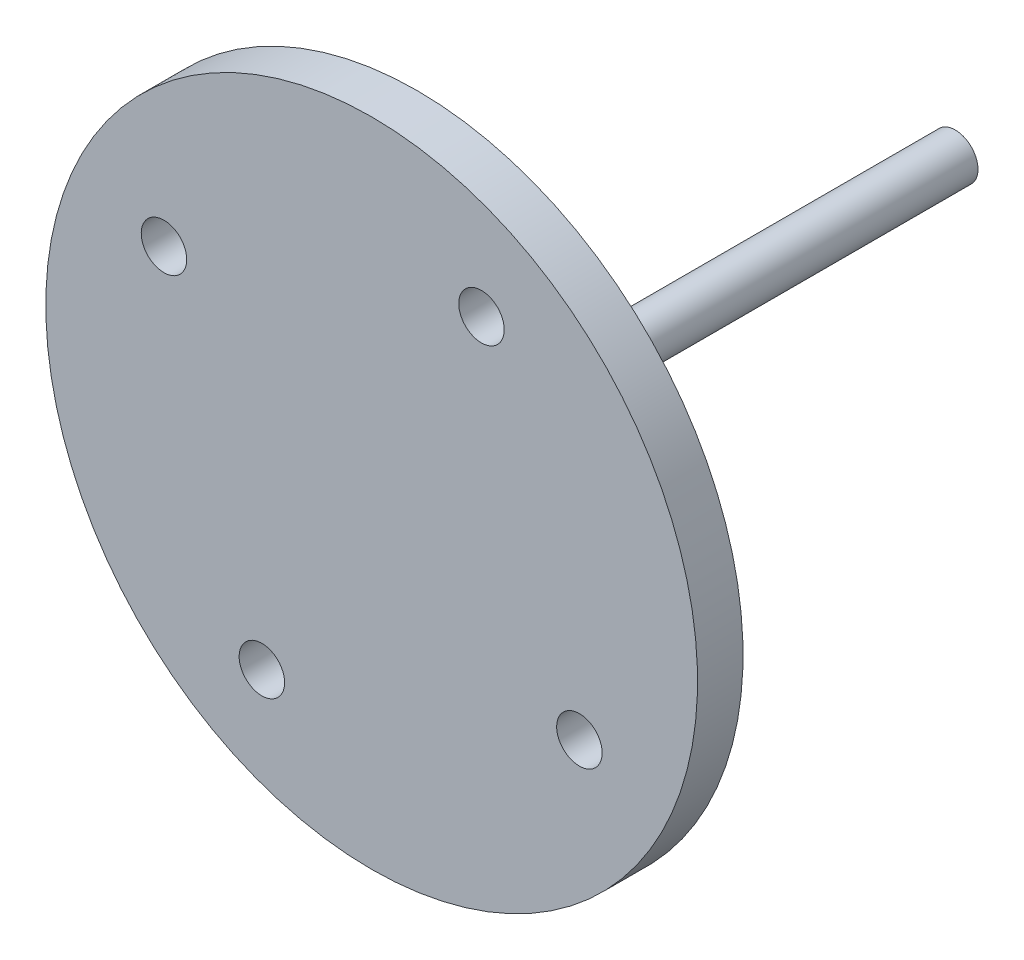
SolidWorks part; units mm, degrees
ref_plane "Front Plane" through (0, 0, 0) normal (0, 0, 1) x (1, 0, 0)
ref_plane "Top Plane" through (0, 0, 0) normal (0, 1, 0) x (1, 0, 0)
ref_plane "Right Plane" through (0, 0, 0) normal (1, 0, 0) x (0, 0, -1)
sketch "Sketch2" plane through (-3.8105, 56.3059, -32.044) normal (0, 0, 1) x (-0.4673, -0.8841, 0)
  circle A0 centre (0, 0) radius 21.5
  circle A1 centre (0, 15.5) radius 1.5
  circle A2 centre (15.5, 0) radius 1.5
  circle A3 centre (0, -15.5) radius 1.5
  circle A4 centre (-15.5, 0) radius 1.5
  point P5 (0, 0)
  point P6 (-1.4184, 3.0878)
  point P7 (-1.4184, 3.0878)
  point P14 (0, 0)
  point P16 (0, 0)
  point P17 (0, 0)
  dimension "D1" = 15.5
  dimension "D3" = 43
  dimension "D4" = 3
  dimension "D2" = 4
extrude "Boss-Extrude1" add sketch "Sketch2" against normal blind 3
sketch "Sketch4" plane through (0, 0, -35.044) normal (0, 0, -1) x (-1, 0, 0)
  circle A0 centre (3.8105, 56.3059) radius 21.5 construction
  circle A1 centre (3.8105, 56.3059) radius 21.5 construction
  circle A2 centre (3.8105, 56.3059) radius 1.5
extrude "Boss-Extrude3" add sketch "Sketch4" along normal blind 35.5
